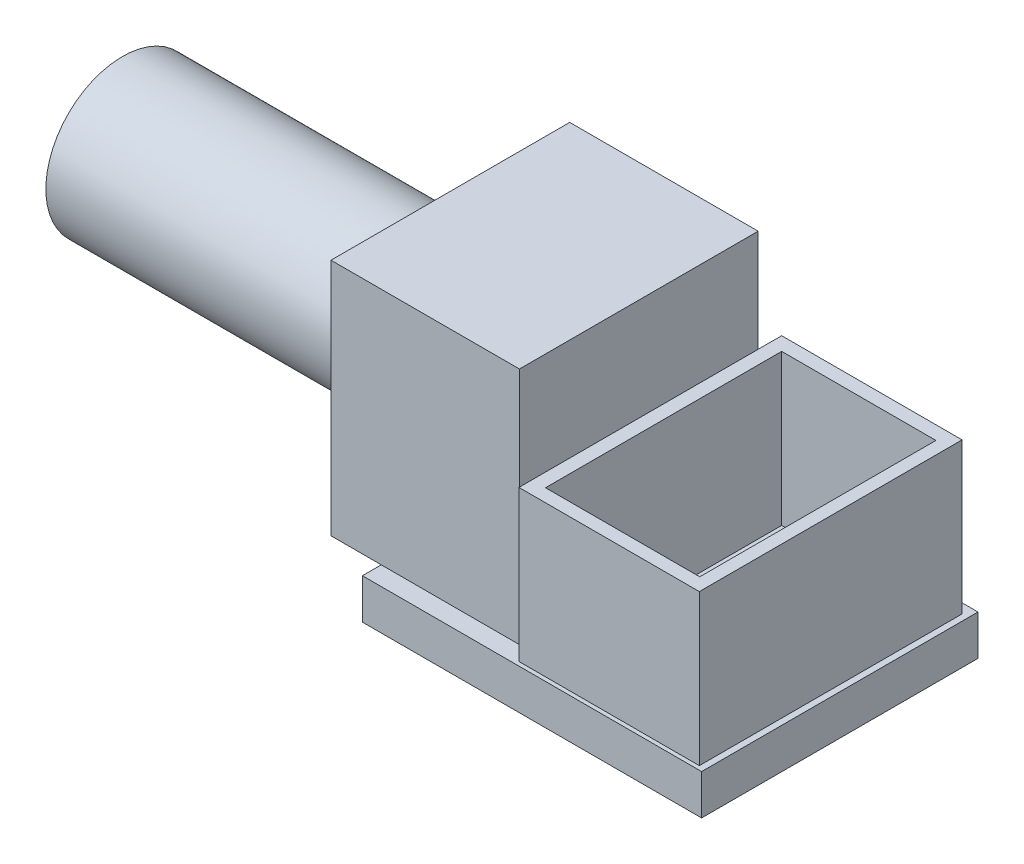
SolidWorks part; units mm, degrees
ref_plane "前视基准面" through (0, 0, 0) normal (0, 0, 1) x (1, 0, 0)
ref_plane "上视基准面" through (0, 0, 0) normal (0, 1, 0) x (1, 0, 0)
ref_plane "右视基准面" through (0, 0, 0) normal (1, 0, 0) x (0, 0, -1)
sketch "草图1" plane through (0, 0, 0) normal (0, 1, 0) x (1, 0, 0)
  line L1 (-13.0891, 5.5485) -> (0.4109, 5.5485)
  line L2 (-13.0891, 5.5485) -> (-13.0891, -5.4515)
  line L3 (-13.0891, -5.4515) -> (0.4109, -5.4515)
  line L4 (0.4109, 5.5485) -> (0.4109, -5.4515)
  dimension "D1" = 11
  dimension "D2" = 13.5
extrude "凸台-拉伸1" add sketch "草图1" along normal blind 1.6
sketch "草图2" plane through (0, 1.6, 0) normal (0, 1, 0) x (1, 0, 0)
  line L0 (-13.0891, 5.5485) -> (-13.0891, -5.4515) construction
  line L1 (-15.0891, 4.7985) -> (-7.5891, 4.7985)
  line L2 (-15.0891, 4.7985) -> (-15.0891, -4.7015)
  line L3 (-15.0891, -4.7015) -> (-7.5891, -4.7015)
  line L4 (-7.5891, 4.7985) -> (-7.5891, -4.7015)
  point P6 (-13.0891, 0.0485)
  point P7 (-15.0891, 0.0485)
  dimension "D1" = 9.5
  dimension "D2" = 7.5
  dimension "D3" = 2
extrude "凸台-拉伸2" add sketch "草图2" along normal blind 9.5
sketch "草图3" plane through (0, 1.6, 0) normal (0, 1, 0) x (1, 0, 0)
  line L1 (-7.0183, 5.1646) -> (0.162, 5.1646)
  line L2 (-7.0183, 5.1646) -> (-7.0183, -5.2937)
  line L3 (-7.0183, -5.2937) -> (0.162, -5.2937)
  line L4 (0.162, 5.1646) -> (0.162, -5.2937)
extrude "凸台-拉伸3" add sketch "草图3" along normal blind 6 contours L2 L1 L4 L3
sketch "草图4" plane through (0, 7.6, 0) normal (0, 1, 0) x (1, 0, 0)
  line L1 (-6.4782, 4.6242) -> (-0.3389, 4.6242)
  line L2 (-6.4782, 4.6242) -> (-6.4782, -4.776)
  line L3 (-6.4782, -4.776) -> (-0.3389, -4.776)
  line L4 (-0.3389, 4.6242) -> (-0.3389, -4.776)
extrude "切除-拉伸1" cut sketch "草图4" against normal blind 6
sketch "草图5" plane through (-15.0891, 0, 0) normal (-1, 0, 0) x (0, 0, 1)
  circle A0 centre (0, 6.2213) radius 3.05
  dimension "D1" = 6.1
extrude "凸台-拉伸4" add sketch "草图5" along normal blind 13
